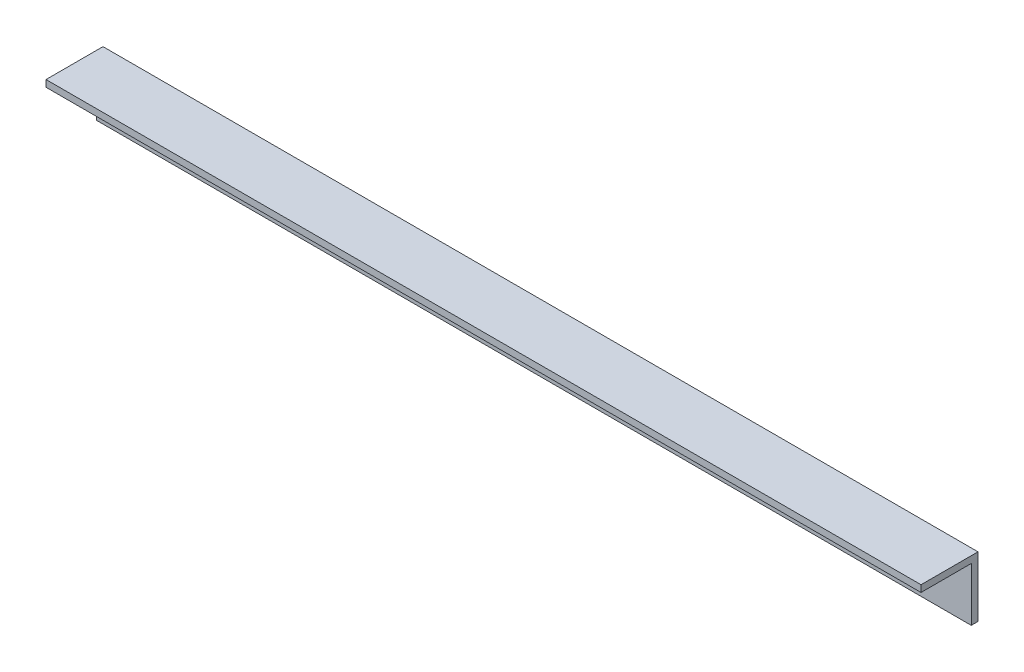
SolidWorks part; units mm, degrees
ref_plane "Alzado" through (0, 0, 0) normal (0, 0, 1) x (1, 0, 0)
ref_plane "Planta" through (0, 0, 0) normal (0, 1, 0) x (1, 0, 0)
ref_plane "Vista lateral" through (0, 0, 0) normal (1, 0, 0) x (0, 0, -1)
sketch "Croquis1" plane through (0, 0, 0) normal (0, 0, 1) x (1, 0, 0)
  line L0 (195, 25.4) -> (-195, -25.4) construction
  line L1 (-195, 25.4) -> (195, 25.4)
  line L2 (-195, 25.4) -> (-195, -25.4)
  line L3 (-195, -25.4) -> (195, -25.4)
  line L4 (195, 25.4) -> (195, -25.4)
  dimension "D1" = 390
  dimension "D2" = 50.8
extrude "Saliente-Extruir1" add sketch "Croquis1" along normal blind 3
sketch "Croquis2" plane through (0, 0, 3) normal (0, 0, 1) x (1, 0, 0)
  line L0 (-195, 0) -> (195, 0) construction
  line L1 (-195, 25.4) -> (-195, -25.4) construction
  line L2 (195, -25.4) -> (195, 25.4) construction
  line L4 (-195, 1.5) -> (195, 1.5)
  line L5 (-195, 1.5) -> (-195, -1.5)
  line L6 (-195, -1.5) -> (195, -1.5)
  line L7 (195, 1.5) -> (195, -1.5)
  dimension "D1" = 1.5
  dimension "D2" = 1.5
extrude "Saliente-Extruir2" add sketch "Croquis2" along normal blind 47.8
sketch "Croquis3" plane through (-195, 0, 0) normal (-1, 0, 0) x (0, 0, 1)
  line L1 (0, 25.4) -> (3, 25.4)
  line L2 (0, 25.4) -> (0, 1.5)
  line L3 (0, 1.5) -> (3, 1.5)
  line L4 (3, 25.4) -> (3, 1.5)
extrude "Cortar-Extruir1" cut sketch "Croquis3" against normal up to surface (390 mm away) up to face at (195, -2.9875, 20.175)
sketch "Croquis4" plane through (0, 1.5, 0) normal (0, 1, 0) x (1, 0, 0)
  line L0 (195, -50.8) -> (195, 0) construction
  line L1 (195, -25.4) -> (-195, -25.4)
  line L2 (195, -25.4) -> (195, -50.8)
  line L3 (195, -50.8) -> (-195, -50.8)
  line L4 (-195, -25.4) -> (-195, -50.8)
extrude "Cortar-Extruir2" cut sketch "Croquis4" against normal up to next
